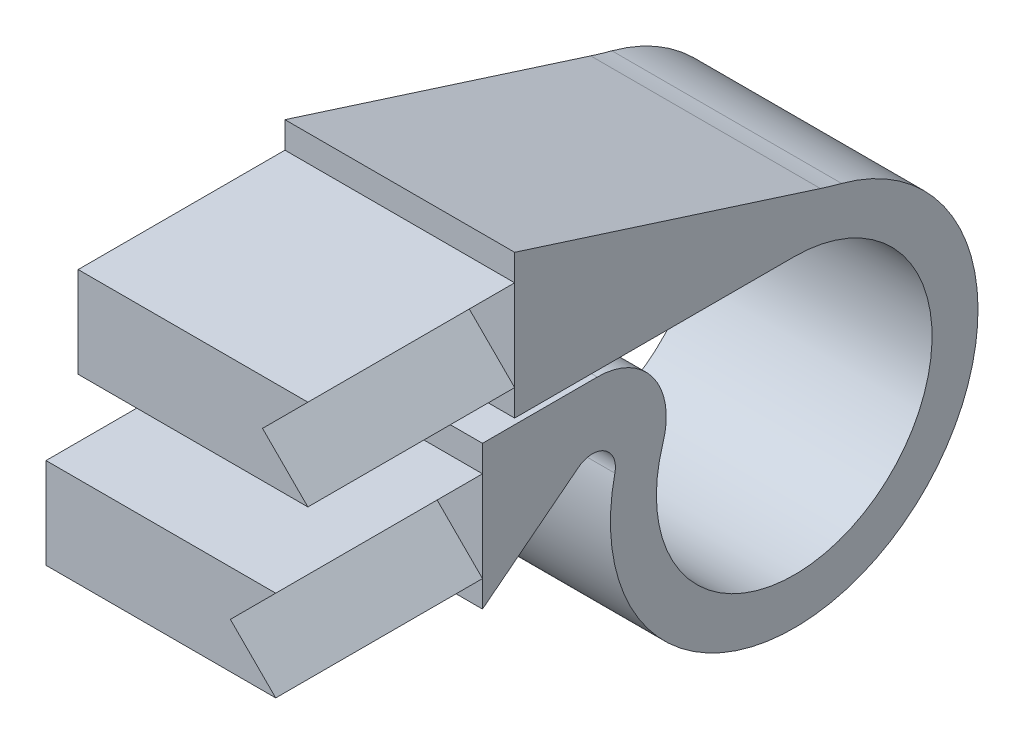
SolidWorks part; units mm, degrees
ref_plane "Front Plane" through (0, 0, 0) normal (0, 0, 1) x (1, 0, 0)
ref_plane "Top Plane" through (0, 0, 0) normal (0, 1, 0) x (1, 0, 0)
ref_plane "Right Plane" through (0, 0, 0) normal (1, 0, 0) x (0, 0, -1)
sketch "Sketch1" plane through (0, 0, 0) normal (1, 0, 0) x (0, 0, -1)
  line L0 (-8.5696, -0.25) -> (-13.5696, -0.25)
  line L1 (0, 0) -> (-12.1696, 0)
  line L6 (1.1396, 2) -> (-12.1696, 6.25)
  line L7 (-12.1696, 6.25) -> (-12.1696, 0)
  line L9 (-13.5696, -6.5) -> (-9.3983, -3.25)
  line L10 (-13.5696, -6.5) -> (-13.5696, -0.25)
  arc A0 (0, 0) -> (-5.713, -4.1667) centre (0, -6) cw
  arc A1 (2.0639, 1.7292) -> (-7.8078, -4.2567) centre (0, -6) cw
  arc A2 (-5.713, -4.1667) -> (-8.5696, -0.25) centre (-8.5696, -3.25) ccw
  arc A3 (-7.8078, -4.2567) -> (-9.3983, -3.25) centre (-8.7837, -4.0388) ccw
  arc A4 (2.0639, 1.7292) -> (1.1396, 2) centre (7.2235, 21.0522) cw
  point P2 (0, 0)
  dimension "D4" = 3
  dimension "D5" = 1
  dimension "D6" = 6
  dimension "D3" = 20
  dimension "D11" = 3
  dimension "D10" = 2
  dimension "D12" = 2
  dimension "D2" = 1.4
  dimension "D7" = 0.25
  dimension "D8" = 6.25
  dimension "D9" = 6.25
  dimension "D13" = 5
extrude "Boss-Extrude1" add sketch "Sketch1" along normal blind 10
sketch "Sketch2" plane through (0, 0, 12.1696) normal (0, 0, 1) x (1, 0, 0)
  line L1 (10, 6.25) -> (0, 6.25) construction
  line L3 (10, 6.25) -> (10, 0) construction
  line L6 (0, 1.15) -> (10, 1.15)
  line L7 (0, 6.25) -> (0, 0) construction
  line L11 (10, 5.1) -> (0, 5.1)
  line L12 (0, 5.1) -> (0, 1.15)
  line L14 (10, 5.1) -> (8.025, 3.125)
  line L15 (8.025, 3.125) -> (10, 1.15)
  line L16 (10, 0) -> (0, 0) construction
  point P10 (0, 3.125)
  dimension "D1" = 1.15
  dimension "D7" = 1.15
extrude "Boss-Extrude4" add sketch "Sketch2" along normal blind 9
sketch "Sketch3" plane through (0, 0, 13.5696) normal (0, 0, 1) x (1, 0, 0)
  line L0 (0, -5.35) -> (10, -5.35)
  line L1 (10, -1.4) -> (0, -1.4)
  line L2 (0, -1.4) -> (0, -5.35)
  line L3 (10, -1.4) -> (8.025, -3.375)
  line L4 (8.025, -3.375) -> (10, -5.35)
  line L5 (10, -0.25) -> (0, -0.25) construction
  line L6 (10, -6.5) -> (0, -6.5) construction
  line L9 (10, -0.25) -> (10, -6.5) construction
  line L10 (0, -0.25) -> (0, -6.5) construction
  point P2 (0, -3.375)
  point P10 (10, -5.35)
  point P13 (10, -1.4)
  point P16 (0, 0)
  dimension "D1" = 1.15
  dimension "D2" = 1.15
extrude "Boss-Extrude5" add sketch "Sketch3" along normal blind 9
